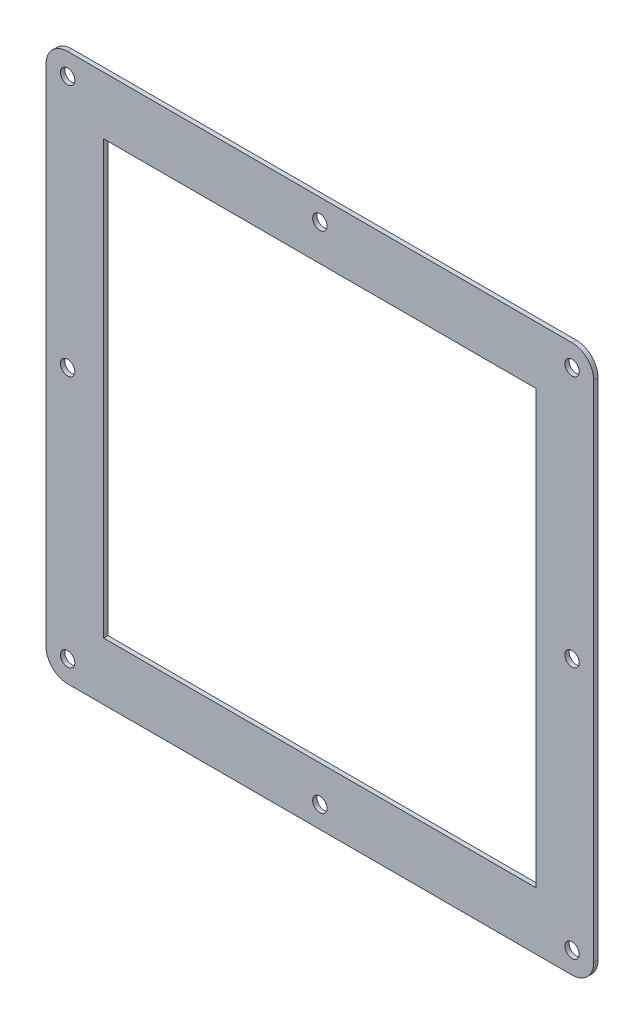
SolidWorks part; units mm, degrees
ref_plane "Front Plane" through (0, 0, 0) normal (0, 0, 1) x (1, 0, 0)
ref_plane "Top Plane" through (0, 0, 0) normal (0, 1, 0) x (1, 0, 0)
ref_plane "Right Plane" through (0, 0, 0) normal (1, 0, 0) x (0, 0, -1)
sketch "Sketch2" plane through (0, 0, 0) normal (0, 0, 1) x (1, 0, 0)
  line L0 (-175, 175) -> (175, 175) construction
  line L1 (-175, 190) -> (175, 190)
  line L2 (-190, 175) -> (-190, -175)
  line L3 (-175, -190) -> (175, -190)
  line L4 (190, 175) -> (190, -175)
  line L5 (-190, 190) -> (190, -190) construction
  line L6 (-190, -190) -> (190, 190) construction
  line L7 (175, 175) -> (175, -175) construction
  line L8 (175, -175) -> (-175, -175) construction
  line L9 (-175, -175) -> (-175, 175) construction
  line L11 (-150, 150) -> (150, 150)
  line L12 (-150, 150) -> (-150, -150)
  line L13 (-150, -150) -> (150, -150)
  line L14 (150, 150) -> (150, -150)
  line L15 (-150, 150) -> (150, -150) construction
  line L16 (-150, -150) -> (150, 150) construction
  arc A0 (-190, -175) -> (-175, -190) centre (-175, -175) ccw
  arc A1 (175, -190) -> (190, -175) centre (175, -175) ccw
  arc A2 (175, 190) -> (190, 175) centre (175, 175) cw
  arc A3 (-175, 190) -> (-190, 175) centre (-175, 175) ccw
  circle A4 centre (-175, 175) radius 5
  circle A5 centre (0, 175) radius 5
  circle A6 centre (175, 175) radius 5
  circle A14 centre (175, 0) radius 5
  circle A15 centre (-175, 0) radius 5
  circle A16 centre (-175, -175) radius 5
  circle A17 centre (0, -175) radius 5
  circle A18 centre (175, -175) radius 5
  point P0 (0, 0)
  point P26 (0, 0)
  dimension "D3" = 15
  dimension "D4" = 10
  dimension "D5" = 10
  dimension "D6" = 10
  dimension "D7" = 300
  dimension "D8" = 10
  dimension "D9" = 10
  dimension "D10" = 10
  dimension "D11" = 10
  dimension "D1" = 380
  dimension "D2" = 380
extrude "Boss-Extrude1" add sketch "Sketch2" along normal blind 3
